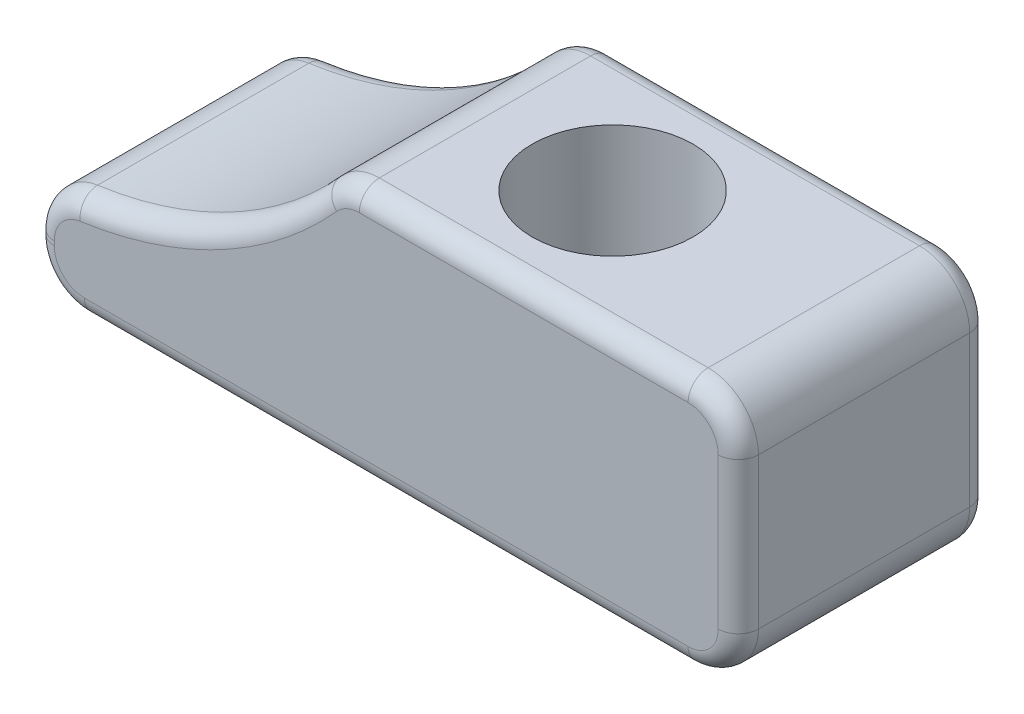
SolidWorks part; units mm, degrees
ref_plane "Plan de face" through (0, 0, 0) normal (0, 0, 1) x (1, 0, 0)
ref_plane "Plan de dessus" through (0, 0, 0) normal (0, 1, 0) x (1, 0, 0)
ref_plane "Plan de droite" through (0, 0, 0) normal (1, 0, 0) x (0, 0, -1)
sketch "Esquisse1" plane through (0, 0, 0) normal (0, 0, 1) x (1, 0, 0)
  line L1 (0, 0) -> (70, 0)
  line L2 (0, 0) -> (0, 25)
  line L3 (0, 25) -> (70, 25)
  line L4 (70, 0) -> (70, 25)
  dimension "D1" = 70
  dimension "D2" = 25
extrude "Boss.-Extru.1" add sketch "Esquisse1" along normal blind 25
sketch "Esquisse2" plane through (0, 0, 25) normal (0, 0, 1) x (1, 0, 0)
  line L0 (0, 0) -> (0, 10) construction
  line L1 (0, 25) -> (0, 0) construction
  line L2 (70, 25) -> (0, 25) construction
  line L3 (30, 25) -> (0, 25)
  line L4 (0, 25) -> (0, 10)
  arc A0 (0, 10) -> (30, 25) centre (-1.2404, 49.9808) ccw
  dimension "D3" = 40
  dimension "D1" = 10
  dimension "D2" = 30
extrude "Enlèv. mat.-Extru.1" cut sketch "Esquisse2" against normal through all both and the other way through all
fillet "Congé1" radius 5 5 edges at (0, 0, 12.5) (30, 25, 12.5) (0, 10, 12.5) (70, 0, 12.5) (70, 25, 12.5)
fillet "Congé2" radius 2 20 edges at (68.5355, 1.4645, 0) (70, 12.5, 0) (68.5355, 23.5355, 0) (48.6589, 25, 0) (30.2753, 24.5638, 0) (17.5982, 14.6947, 0) (1.2273, 8.6968, 0) (0, 5.2078, 0) (1.4645, 1.4645, 0) (35, 0, 0) (1.2273, 8.6968, 25) (17.5982, 14.6947, 25) (30.2753, 24.5638, 25) (48.6589, 25, 25) (68.5355, 23.5355, 25) (70, 12.5, 25) (68.5355, 1.4645, 25) (35, 0, 25) (1.4645, 1.4645, 25) (0, 5.2078, 25)
sketch "Esquisse3" plane through (0, 25, 0) normal (0, 1, 0) x (1, 0, 0)
  line L0 (70, -12.5) -> (45, -12.5) construction
  line L1 (70, -2) -> (70, -23) construction
  circle A0 centre (45, -12.5) radius 8
  dimension "D1" = 16
  dimension "D2" = 25
extrude "Enlèv. mat.-Extru.2" cut sketch "Esquisse3" against normal through all both and the other way through all
